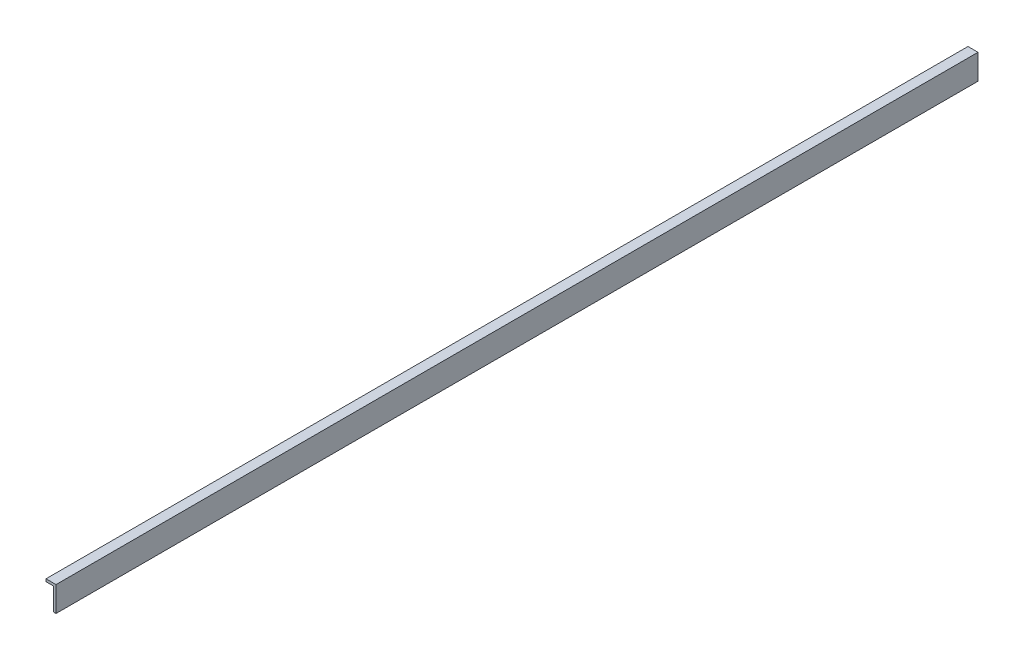
SolidWorks part; units mm, degrees
ref_plane "Front Plane" through (0, 0, 0) normal (0, 0, 1) x (1, 0, 0)
ref_plane "Top Plane" through (0, 0, 0) normal (0, 1, 0) x (1, 0, 0)
ref_plane "Right Plane" through (0, 0, 0) normal (1, 0, 0) x (0, 0, -1)
other "Configuration Table"
sketch "Sketch1" plane through (0, 0, 0) normal (0, 0, 1) x (1, 0, 0)
  line L0 (501.5, 404.5) -> (503.5, 404.5)
  line L1 (503.5, 404.5) -> (503.5, 424.5)
  line L2 (503.5, 424.5) -> (495.5, 424.5)
  line L3 (495.5, 424.5) -> (495.5, 422.5)
  line L4 (495.5, 422.5) -> (501.5, 422.5)
  line L5 (501.5, 422.5) -> (501.5, 404.5)
extrude "STORE_kaset_L_raf_3_sag_1" add sketch "Sketch1" against normal blind 735.5 from offset 20 separate body
